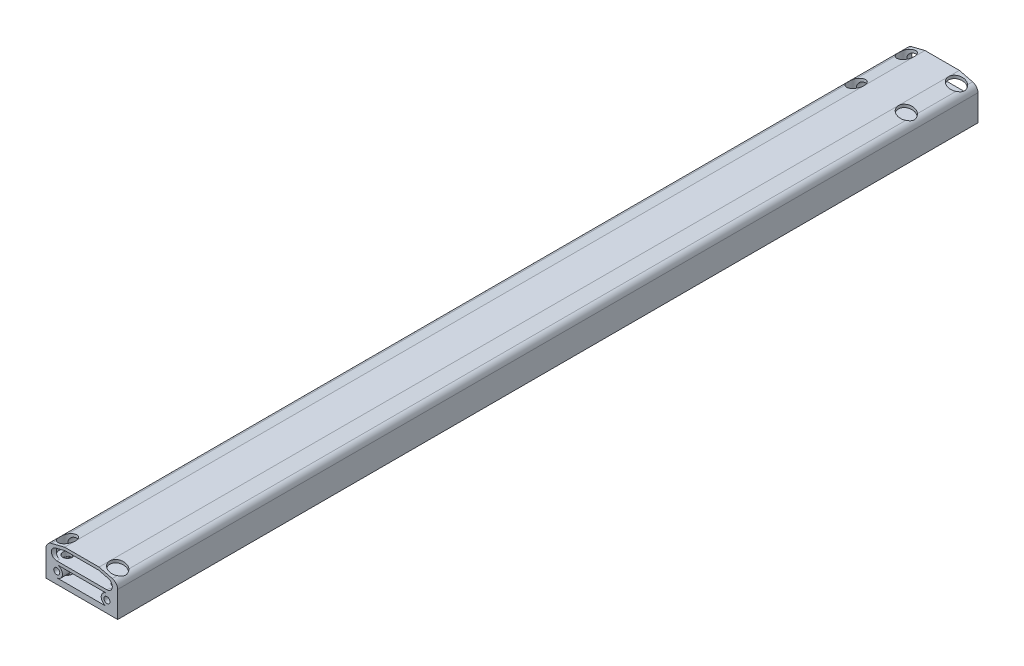
SolidWorks part; units mm, degrees
ref_plane "前视基准面" through (0, 0, 0) normal (0, 0, 1) x (1, 0, 0)
ref_plane "上视基准面" through (0, 0, 0) normal (0, 1, 0) x (1, 0, 0)
ref_plane "右视基准面" through (0, 0, 0) normal (1, 0, 0) x (0, 0, -1)
sketch "草图1" plane through (0, 0, 0) normal (0, 0, 1) x (1, 0, 0)
  line L1 (-25, 25.2) -> (25, 25.2)
  line L2 (-25, 25.2) -> (-25, 0)
  line L3 (-25, 0) -> (25, 0)
  line L4 (25, 25.2) -> (25, 0)
  dimension "D1" = 25.2
  dimension "D2" = 50
extrude "凸台-拉伸1" add sketch "草图1" along normal mid plane 600
sketch "草图2" plane through (0, 0, 300) normal (0, 0, 1) x (1, 0, 0)
  line L0 (-12, 25.2) -> (-21.2118, 22.9032)
  line L1 (25, 25.2) -> (-25, 25.2) construction
  line L2 (-25, 25.2) -> (-25, 0) construction
  line L3 (-25, 18.2) -> (-25, 25.2)
  line L4 (-25, 25.2) -> (-12, 25.2)
  line L5 (0, 0) -> (0, 30.2472) construction
  line L6 (25, 25.2) -> (12, 25.2)
  line L7 (25, 18.2) -> (25, 25.2)
  line L8 (12, 25.2) -> (21.2118, 22.9032)
  line L9 (-11.7544, 23.2) -> (11.7544, 23.2)
  line L10 (11.7544, 23.2) -> (18.4016, 21.5427)
  line L11 (17.5, 14.2) -> (-17.5, 14.2)
  line L12 (-18.4016, 21.5427) -> (-11.7544, 23.2)
  arc A0 (-21.2118, 22.9032) -> (-25, 18.2) centre (-20.0022, 18.0518) ccw
  arc A1 (21.2118, 22.9032) -> (25, 18.2) centre (20.0022, 18.0518) cw
  arc A2 (18.4016, 21.5427) -> (17.5, 14.2) centre (17.5, 17.9267) cw
  arc A3 (-17.5, 14.2) -> (-18.4016, 21.5427) centre (-17.5, 17.9267) cw
  dimension "D3" = 5
  dimension "D1" = 24
  dimension "D2" = 7
  dimension "D4" = 14
  dimension "D5" = 2
  dimension "D6" = 9
  dimension "D7" = 2
  dimension "D8" = 35
extrude "切除-拉伸1" cut sketch "草图2" against normal through all
sketch "草图3" plane through (0, 0, 300) normal (0, 0, 1) x (1, 0, 0)
  line L0 (0, 0) -> (0, 18.4749) construction
  line L1 (-25, 0) -> (25, 0) construction
  line L2 (-17.5, 12) -> (17.5, 12)
  line L3 (-17.5, 8) -> (-4.6664, 8) construction
  line L4 (-17.5, 4) -> (17.5, 4)
  circle A0 centre (-17.5, 8) radius 1.9
  circle A1 centre (17.5, 8) radius 1.9
  arc A2 (17.5, 12) -> (17.5, 4) centre (17.5, 8) ccw
  arc A3 (-17.5, 12) -> (-17.5, 4) centre (-17.5, 8) cw
  dimension "D3" = 3.8
  dimension "D5" = 4
  dimension "D1" = 35
  dimension "D2" = 8
  dimension "D4" = 8
extrude "切除-拉伸2" cut sketch "草图3" against normal through all
hole_wizard "M5x0.8 螺纹孔1" positions "草图5" profile "草图4" tap size "M5x0.8" standard "JIS"
sketch "草图5" plane through (0, 0, 300) normal (0, 0, 1) x (1, 0, 0)
  point P1 (-17.5, 8)
  point P4 (17.5, 8)
sketch "草图4" plane through (-17.5, 8, 300) normal (1, 0, 0) x (0, -1, 0)
  line L0 (0, 0) -> (0, 13.6618)
  line L1 (0, 13.6618) -> (2.1, 12.4)
  line L2 (2.1, 12.4) -> (2.1, 0)
  line L5 (2.1, 0) -> (0, 0)
  line L10 (0, 13.6618) -> (-2.1, 12.4) construction
  line L11 (0, -6.35) -> (0, 107.95) construction
  dimension "螺纹孔钻头直径" = 4.2
  dimension "螺纹孔钻头深度" = 12.4
  dimension "导头角度" = 118
cosmetic thread "孔螺蚊线1" parameters "D1"=10, "D2"=5
cosmetic thread "孔螺蚊线2" parameters "D1"=10, "D2"=5
mirror "镜向1" about plane through (0, 0, 0) normal (0, 0, 1) of "M5x0.8 螺纹孔1"
sketch "草图6" plane through (0, 25.2, 0) normal (0, 1, 0) x (1, 0, 0)
  line L0 (0, 300) -> (0, 210.7902) construction
  line L1 (12, 300) -> (-12, 300) construction
  line L2 (12, -300) -> (-12, -300) construction
  circle A0 centre (-17.5, 292.5) radius 5.5
  circle A1 centre (-17.5, 257.5) radius 5.5
  circle A2 centre (-17.5, -292.5) radius 5.5
  circle A3 centre (17.5, -292.5) radius 5.5
  circle A4 centre (17.5, 257.5) radius 5.5
  circle A5 centre (17.5, 292.5) radius 5.5
  dimension "D5" = 11
  dimension "D1" = 35
  dimension "D2" = 7.5
  dimension "D3" = 35
  dimension "D4" = 7.5
extrude "切除-拉伸3" cut sketch "草图6" against normal up to surface (11 mm away) up to face at (0, 14.2, 0)
sketch "草图7" plane through (0, 14.2, 0) normal (0, 1, 0) x (1, 0, 0)
  circle A0 centre (-17.5, 292.5) radius 3.25
  circle A1 centre (-17.5, 257.5) radius 3.25
  circle A2 centre (-17.5, -292.5) radius 3.25
  circle A3 centre (17.5, -292.5) radius 3.25
  circle A4 centre (17.5, 257.5) radius 3.25
  circle A5 centre (17.5, 292.5) radius 3.25
  dimension "D1" = 6.5
extrude "切除-拉伸4" cut sketch "草图7" against normal through all
sketch "草图8" plane through (0, 0, 0) normal (0, -1, 0) x (1, 0, 0)
  line L0 (0, -300) -> (0, -250) construction
  line L1 (-25, -300) -> (25, -300) construction
  line L2 (-10, -300) -> (-10, -250)
  line L3 (10, -300) -> (10, -250)
  arc A0 (-10, -300) -> (10, -300) centre (0, -300) ccw
  arc A1 (10, -250) -> (-10, -250) centre (0, -250) ccw
  point P5 (0, -275)
  dimension "D2" = 10
  dimension "D1" = 50
extrude "切除-拉伸5" cut sketch "草图8" against normal blind 3
